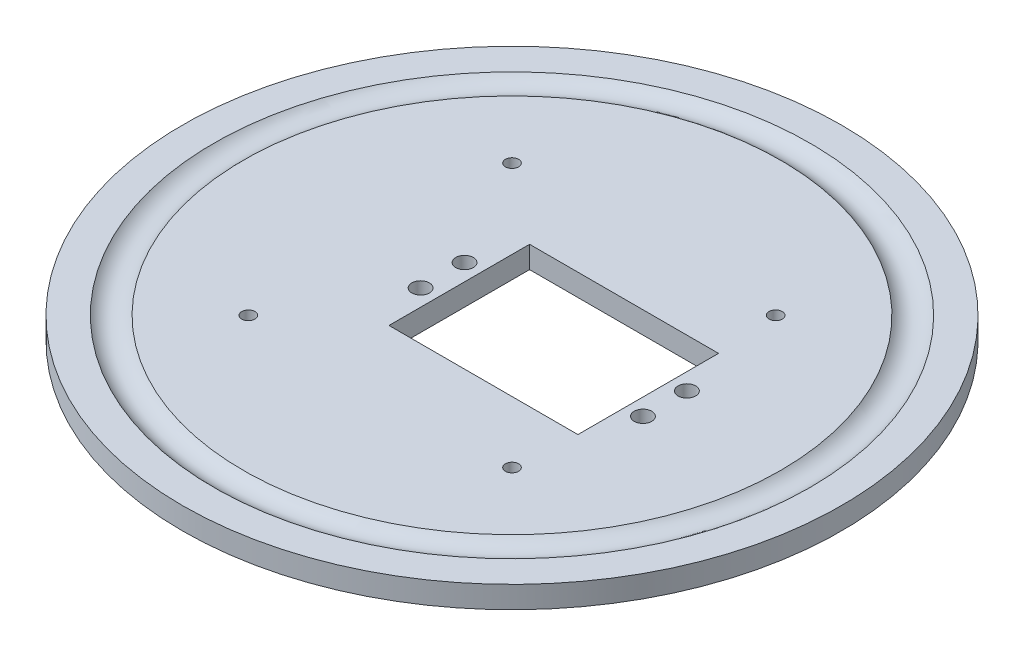
SolidWorks part; units mm, degrees
ref_plane "Alzado" through (0, 0, 0) normal (0, 0, 1) x (1, 0, 0)
ref_plane "Planta" through (0, 0, 0) normal (0, 1, 0) x (1, 0, 0)
ref_plane "Vista lateral" through (0, 0, 0) normal (1, 0, 0) x (0, 0, -1)
sketch "Croquis1" plane through (0, 0, 0) normal (0, 1, 0) x (1, 0, 0)
  circle A0 centre (0, 0) radius 75
  dimension "D1" = 150
extrude "Saliente-Extruir1" add sketch "Croquis1" along normal blind 5
sketch "Croquis2" plane through (0, 5, 0) normal (0, 1, 0) x (1, 0, 0)
  line L0 (0, 0) -> (31, 0)
  line L1 (31, 0) -> (-12, 0)
  line L2 (-12, 0) -> (-12, 13)
  line L3 (-12, 13) -> (-12, -13)
  line L5 (-12, 13) -> (31, 13)
  line L6 (-12, 13) -> (-12, -13)
  line L7 (-12, -13) -> (31, -13)
  line L8 (31, 13) -> (31, -13)
  dimension "D1" = 31
  dimension "D2" = 43
  dimension "D3" = 13
  dimension "D4" = 26
  dimension "D5" = 0
extrude "Cortar-Extruir1" cut sketch "Croquis2" against normal blind 5 contours L8 L0 L1 L3 L7 | L8 L5 L2 L1 L0
sketch "Croquis4" plane through (0, 5, 0) normal (0, 1, 0) x (1, 0, 0)
  line L1 (-30, -30) -> (30, -30)
  line L2 (-30, -30) -> (-30, 30)
  line L3 (-30, 30) -> (30, 30)
  line L4 (30, -30) -> (30, 30)
  line L5 (-30, -30) -> (30, 30) construction
  line L6 (-30, 30) -> (30, -30) construction
  circle A0 centre (-30, 30) radius 1.5
  circle A1 centre (30, 30) radius 1.5
  circle A2 centre (30, -30) radius 1.5
  circle A3 centre (-30, -30) radius 1.5
  point P0 (0, 0)
  dimension "D3" = 3
  dimension "D4" = 3
  dimension "D5" = 3
  dimension "D6" = 3
  dimension "D1" = 60
  dimension "D2" = 60
extrude "Cortar-Extruir2" cut sketch "Croquis4" against normal blind 5 contours L3 A0 L2 | L2 A0 L3 | L4 A1 L3 | L3 A1 L4 | L4 A2 L1 | L1 A2 L4 | L1 A3 L2 | L2 A3 L1
sketch "Croquis5" plane through (0, 5, 0) normal (0, 1, 0) x (1, 0, 0)
  circle A0 centre (0, 0) radius 64.5
  dimension "D1" = 129
sketch "Croquis6" plane through (0, 0, 0) normal (0, 0, 1) x (1, 0, 0)
  line L0 (0, 5) -> (64.5, 5)
  line L1 (64.5, 5) -> (-64.5, 5) construction
  line L2 (75, 5) -> (-75, 5) construction
  line L3 (64.5, 5) -> (64.5, 8)
  circle A0 centre (64.5, 8) radius 4.5
  dimension "D3" = 9
  dimension "D1" = 64.5
  dimension "D2" = 3
sweep "Cortar-Barrer3" cut profiles "Croquis6" path "Croquis5"
sketch "Croquis11" plane through (0, 5, 0) normal (0, 1, 0) x (1, 0, 0)
  line L1 (-12, 13) -> (31, 13)
  line L2 (-12, 13) -> (-12, 16)
  line L3 (-12, 16) -> (31, 16)
  line L4 (31, 13) -> (31, 16)
  line L5 (-12, -13) -> (31, -13)
  line L6 (-12, -13) -> (-12, -16)
  line L7 (-12, -16) -> (31, -16)
  line L8 (31, -13) -> (31, -16)
  dimension "D1" = 43
  dimension "D2" = 3
  dimension "D3" = 3
  dimension "D4" = 43
extrude "Cortar-Extruir3" cut sketch "Croquis11" against normal blind 5
sketch "Croquis12" plane through (0, 5, 0) normal (0, 1, 0) x (1, 0, 0)
  line L0 (31, 0) -> (34.8, 0)
  line L1 (31, 16) -> (31, -16) construction
  line L2 (34.8, 0) -> (34.8, -5)
  line L3 (34.8, -5) -> (34.8, 5)
  line L4 (-12, 0) -> (-15.8, 0)
  line L5 (-12, 16) -> (-12, -16) construction
  line L6 (-15.8, 0) -> (-15.8, 5)
  line L7 (-15.8, 5) -> (-15.8, -5)
  circle A0 centre (34.8, 5) radius 2
  circle A1 centre (34.8, -5) radius 2
  circle A2 centre (-15.8, -5) radius 2
  circle A3 centre (-15.8, 5) radius 2
  point P19 (-17.8827, -0.3827)
  dimension "D4" = 4
  dimension "D5" = 4
  dimension "D6" = 4
  dimension "D7" = 4
  dimension "D1" = 3.8
  dimension "D2" = 10
  dimension "D3" = 5
  dimension "D8" = 5
  dimension "D9" = 10
  dimension "D10" = 3.8
extrude "Cortar-Extruir4" cut sketch "Croquis12" against normal blind 5
